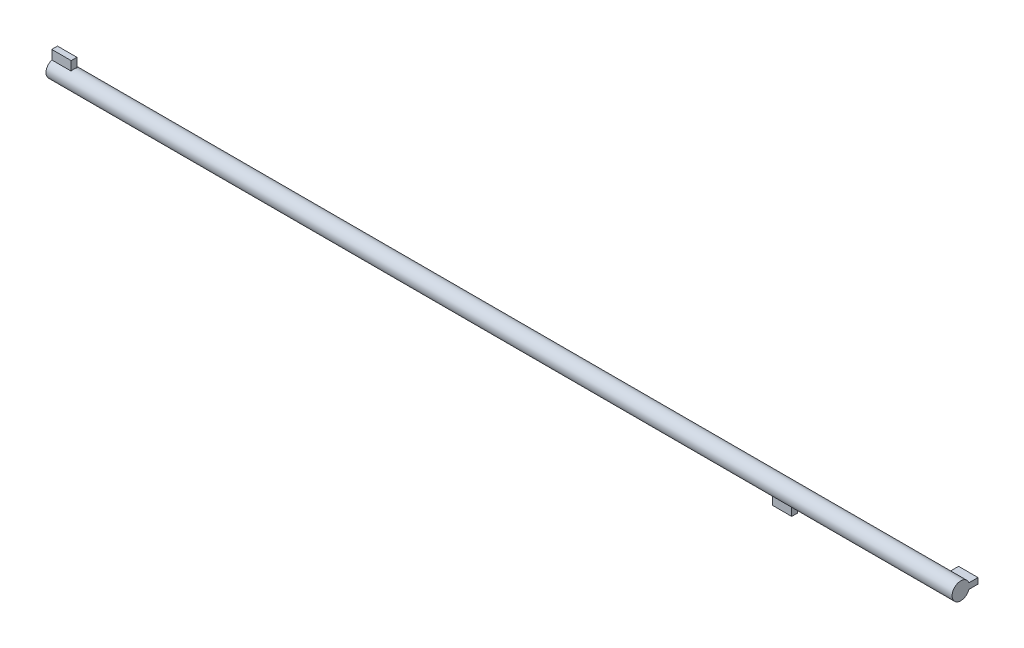
SolidWorks part; units mm, degrees
ref_plane "Front Plane" through (0, 0, 0) normal (0, 0, 1) x (1, 0, 0)
ref_plane "Top Plane" through (0, 0, 0) normal (0, 1, 0) x (1, 0, 0)
ref_plane "Right Plane" through (0, 0, 0) normal (1, 0, 0) x (0, 0, -1)
sketch "Sketch1" plane through (0, 0, 0) normal (1, 0, 0) x (0, 0, -1)
  circle A0 centre (0, 0) radius 2
  dimension "D1" = 4
extrude "Shaft" add sketch "Sketch1" along normal blind 43 and the other way blind 167
sketch "Sketch6" plane through (0, 0, 0) normal (1, 0, 0) x (0, 0, -1)
  line L0 (0, 2) -> (0, -2) construction
  line L1 (-0.6667, 0) -> (0.6667, 0)
  line L2 (-0.6667, 0) -> (-0.6667, -4)
  line L3 (0.6667, 0) -> (0.6667, -4)
  line L4 (-0.6667, -4) -> (0.6667, -4)
  line L5 (0.6667, 0) -> (2, 0) construction
  line L6 (-0.6667, 0) -> (-2, 0) construction
  circle A0 centre (0, 0) radius 2 construction
sketch "Sketch2" plane through (-167, 0, 0) normal (-1, 0, 0) x (0, 0, 1)
  line L4 (0, 2) -> (0, -2) construction
  line L5 (-0.6667, 0) -> (0.6667, 0)
  line L6 (-0.6667, 0) -> (-0.6667, 4)
  line L7 (0.6667, 0) -> (0.6667, 4)
  line L8 (-0.6667, 4) -> (0.6667, 4)
  line L9 (0.6667, 0) -> (2, 0) construction
  line L10 (-0.6667, 0) -> (-2, 0) construction
  circle A1 centre (0, 0) radius 2 construction
extrude "Shaft M" add sketch "Sketch2" against normal blind 4.5
sketch "Sketch4" plane through (43, 0, 0) normal (1, 0, 0) x (0, 0, -1)
  line L0 (-2, 0) -> (2, 0) construction
  line L2 (0, 0.6667) -> (0, -0.6667)
  line L3 (0, 0.6667) -> (4, 0.6667)
  line L4 (0, -0.6667) -> (4, -0.6667)
  line L5 (4, 0.6667) -> (4, -0.6667)
  line L6 (0, 0.6667) -> (0, 2) construction
  line L7 (0, -0.6667) -> (0, -2) construction
  circle A0 centre (0, 0) radius 2 construction
extrude "Shaft R" add sketch "Sketch4" against normal blind 4.5
extrude "Shaft L" add sketch "Sketch6" along normal blind 4.5
